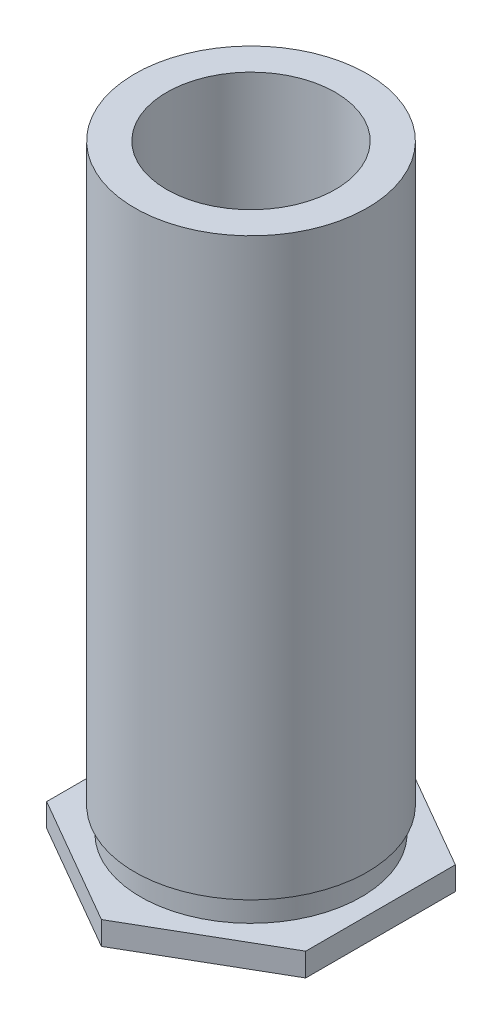
SolidWorks part; units mm, degrees
revolve "Body" add sketch "BodySke"
sketch "BodySke" plane through (0, 0, 0) normal (0, 0, 1) x (1, 0, 0)
  line L0 (3.556, 0) -> (4.5964, 0)
  line L1 (4.5964, 0) -> (4.5964, 0.7112)
  line L2 (4.5964, 0.7112) -> (3.3782, 0.7112)
  line L3 (1.9406, 19.05) -> (1.9406, 0.0051)
  line L4 (3.556, 1.458) -> (3.3782, 1.458)
  line L5 (3.3782, 1.458) -> (3.3782, 0.7112)
  line L6 (3.556, 0.0025) -> (3.556, 0)
  line L7 (1.016, 18.2575) -> (3.6522, 18.2575) construction
  line L8 (3.556, 19.05) -> (1.9406, 19.05)
  line L9 (0, 0) -> (0, 15.24) construction
  line L10 (3.556, 0.0025) -> (0, 0.0025)
  line L11 (3.556, 19.05) -> (3.556, 1.458)
  line L12 (0, 0.0051) -> (1.9406, 0.0051)
  line L13 (0, 0.0051) -> (0, 0.0025)
  line L14 (1.016, 0.0051) -> (3.6522, 0.0051) construction
  line L15 (1.016, 0) -> (3.6522, 0) construction
  dimension "E_dia" = 9.1928
  dimension "Thread_min" = 3.8811
  dimension "C_dia" = 7.112
  dimension "Thread_limit" = 19.0449
  dimension "Advance" = 0.7925
  dimension "Thread_depth" = 19.0449
  dimension "Drill_depth" = 19.05
  dimension "Length" = 19.05
  dimension "Clinching_ht" = 0.7112
  dimension "Groove_wid" = 0.7468
  dimension "Groove_dia" = 6.7564
  dimension "D1" = 0.0025
cosmetic thread "ThreadCosmetic" [suppressed]
revolve "EndChamfer" cut sketch "EndChamferSke" angle 360 about L0
sketch "EndChamferSke" plane through (0, 0, 0) normal (0, 0, 1) x (1, 0, 0)
  line L0 (0, -2.54) -> (0, 7.62) construction
  line L1 (0, 0) -> (0, 15.24) construction
  line L2 (2.5781, 11.1252) -> (2.5781, 19.304)
  line L4 (2.5781, 11.1252) -> (2.413, 11.1252)
  line L6 (2.413, 11.1252) -> (1.9406, 10.7945)
  line L8 (1.9406, 10.7945) -> (1.9406, 19.304)
  line L9 (2.5781, 19.304) -> (1.9406, 19.304)
  line L10 (3.556, 19.05) -> (-3.556, 19.05) construction
  dimension "D1" = 0.254
  dimension "Thread_nominal" = 4.826
  dimension "D2" = 34.99
  dimension "Thread_min" = 3.8811
  dimension "Inset" = 7.9248
  dimension "B_dia" = 5.1562
revolve "TapDrill" cut sketch "TapDriSke" angle 360 about L0
sketch "TapDriSke" plane through (0, 0, 0) normal (0, 0, 1) x (1, 0, 0)
  line L0 (0, 0) -> (0, 15.24) construction
  line L1 (0, 0) -> (0, 15.24) construction
  line L2 (1.9406, -3.9573) -> (1.9406, 19.05)
  line L3 (3.556, 19.05) -> (-3.556, 19.05) construction
  line L4 (1.9406, -3.9573) -> (0, -4.7611)
  line L5 (0, -4.7611) -> (0, 19.05)
  line L6 (0, 19.05) -> (1.9406, 19.05)
  line L7 (1.9406, 0.0051) -> (1.9406, 19.05) construction
  line L8 (0, -4.7611) -> (-1.9406, -3.9573) construction
  line L9 (-1.9406, 19.05) -> (-1.9406, 0.0051) construction
  dimension "D1" = 135
ref_plane "Plane1" through (0, 0, 0) normal (0, 0, 1) x (1, 0, 0)
ref_plane "Plane2" through (0, 0, 0) normal (0, 1, 0) x (1, 0, 0)
ref_plane "Plane3" through (0, 0, 0) normal (1, 0, 0) x (0, 0, -1)
ref_plane "Plane4" through (0, -0.5486, 0) normal (0, 1, 0) x (-1, 0, 0)
sketch "ThdSchSke" plane through (0, 0, 0) normal (0, 0, 1) x (1, 0, 0)
  line L0 (0, -5.08) -> (0, 7.62) construction
  line L1 (0, 0) -> (0, 15.24) construction
  line L2 (0, 11.1252) -> (2.413, 11.1252) construction
  line L4 (2.413, 11.1252) -> (1.9406, 11.456)
  line L5 (2.5781, 11.1252) -> (-2.5781, 11.1252) construction
  line L6 (2.413, 11.1252) -> (1.9406, 10.7944)
  line L7 (1.9406, 11.456) -> (1.9406, 10.7944)
  dimension "Thread_min" = 3.8811
revolve "ThreadSchematic" [suppressed] cut sketch "ThdSchSke" angle 360 about L0
pattern_linear "ThdSchPat" [suppressed]
sketch "HexDieSke" plane through (0, 0.7112, 0) normal (0, 1, 0) x (-1, 0, 0)
  line L0 (0, 4.5754) -> (3.9624, 2.2877)
  line L1 (3.9624, 2.2877) -> (3.9624, -2.2877)
  line L2 (3.9624, -2.2877) -> (0, -4.5754)
  line L3 (0, -4.5754) -> (-3.9624, -2.2877)
  line L4 (-3.9624, -2.2877) -> (-3.9624, 2.2877)
  line L5 (-3.9624, 2.2877) -> (0, 4.5754)
  circle A1 centre (0, 0) radius 3.9624 construction
  circle A2 centre (0, 0) radius 4.5754 construction
  circle A3 centre (0, 0) radius 4.6091
  dimension "Width_across_flats" = 7.9248
  dimension "OD" = 9.2182
extrude "HexDie" cut sketch "HexDieSke" against normal blind 0.7112
equation "' \"Length@BodySke\" = 0.75"
equation "' \"B_dia@EndChamferSke\" = 0.203"
equation "' \"C_dia@BodySke\" = 0.28"
equation "' \"Width_across_flats@HexDieSke\" = 0.312"
equation "' \"Inset@EndChamferSke\" = 0.312"
equation "' \"Advance@BodySke\" = 0.0312"
equation "' \"Thread_min@BodySke\" = 0.1528"
equation "' \"Thread_nominal@ThreadCosmetic\" = 0.19"
equation "\"E_dia@BodySke\" = \"Width_across_flats@HexDieSke\" * 1.16"
equation "\"Drill_depth@BodySke\" = \"Length@BodySke\""
equation "\"Thread_depth@BodySke\" = \"Length@BodySke\" - 0.0002"
equation "\"Clinching_ht@BodySke\" = \"C_dia@BodySke\" * 0.1"
equation "\"Groove_dia@BodySke\" = \"C_dia@BodySke\" * 0.95"
equation "\"Groove_wid@BodySke\" = \"Clinching_ht@BodySke\" * 1.05"
equation "\"Thread_limit@BodySke\" = ((sgn( \"Length@BodySke\" - \"Thread_depth@BodySke\" )-1)*( \"Length@BodySke\" - \"Thread_depth@BodySke\" ))/-2+ \"Thread_depth@BodySke\""
equation "\"Depth@TapDriSke\" = \"Thread_limit@BodySke\" + \"Advance@BodySke\" * 5"
equation "\"Depth@TapDriSke\" = ((sgn( \"Depth@TapDriSke\" - \"Drill_depth@BodySke\" )+1)*( \"Depth@TapDriSke\" - \"Drill_depth@BodySke\" ))/2 +\"Drill_depth@BodySke\""
equation "\"Depth@HexDie\" = \"Clinching_ht@BodySke\""
equation "\"OD@HexDieSke\" =  \"Width_across_flats@HexDieSke\" * 1.16 + 0.001"
equation "\"Thread_nominal@EndChamferSke\" = \"Thread_nominal@ThreadCosmetic\""
equation "\"Thread_min@EndChamferSke\" = \"Thread_min@BodySke\""
equation "\"D2@EndChamferSke\" = \"Vee_angle@ThdSchSke\" / 2 - 0.01"
equation "\"Thread_nominal@ThdSchSke\" = \"Thread_nominal@ThreadCosmetic\""
equation "\"Thread_min@ThdSchSke\" = \"Thread_min@BodySke\""
equation "\"Num_threads@ThdSchPat\" = int(  ( \"Thread_limit@BodySke\" - \"Inset@EndChamferSke\" ) / \"Advance@BodySke\" + 0.999 )  + 1"
equation "\"Advance@ThdSchPat\" = (  \"Thread_limit@BodySke\" - \"Inset@EndChamferSke\" ) /  (\"Num_threads@ThdSchPat\" - 1) 'relax it"
